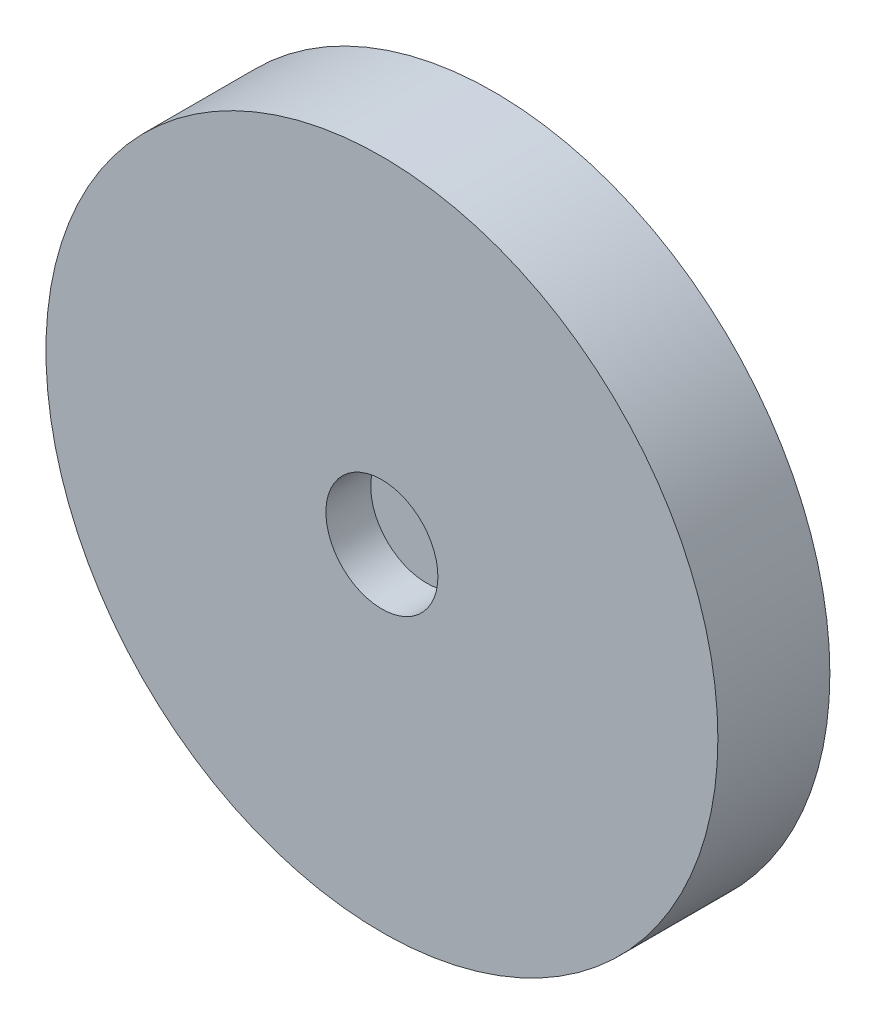
SolidWorks part; units mm, degrees
ref_plane "Plan de face" through (0, 0, 0) normal (0, 0, 1) x (1, 0, 0)
ref_plane "Plan de dessus" through (0, 0, 0) normal (0, 1, 0) x (1, 0, 0)
ref_plane "Plan de droite" through (0, 0, 0) normal (1, 0, 0) x (0, 0, -1)
sketch "Esquisse1" plane through (0, 0, 0) normal (0, 0, 1) x (1, 0, 0)
  circle A0 centre (0, 0) radius 15
  dimension "D1" = 30
extrude "Boss.-Extru.1" add sketch "Esquisse1" along normal blind 5
sketch "Esquisse2" plane through (0, 0, 0) normal (0, 0, -1) x (-1, 0, 0)
  circle A0 centre (0, 0) radius 1
  dimension "D1" = 2
extrude "Boss.-Extru.2" add sketch "Esquisse2" along normal blind 3
sketch "Esquisse3" plane through (0, 0, 5) normal (0, 0, 1) x (1, 0, 0)
  circle A0 centre (0, 0) radius 2.5
  dimension "D1" = 5
extrude "Enlèv. mat.-Extru.2" cut sketch "Esquisse3" against normal blind 2
